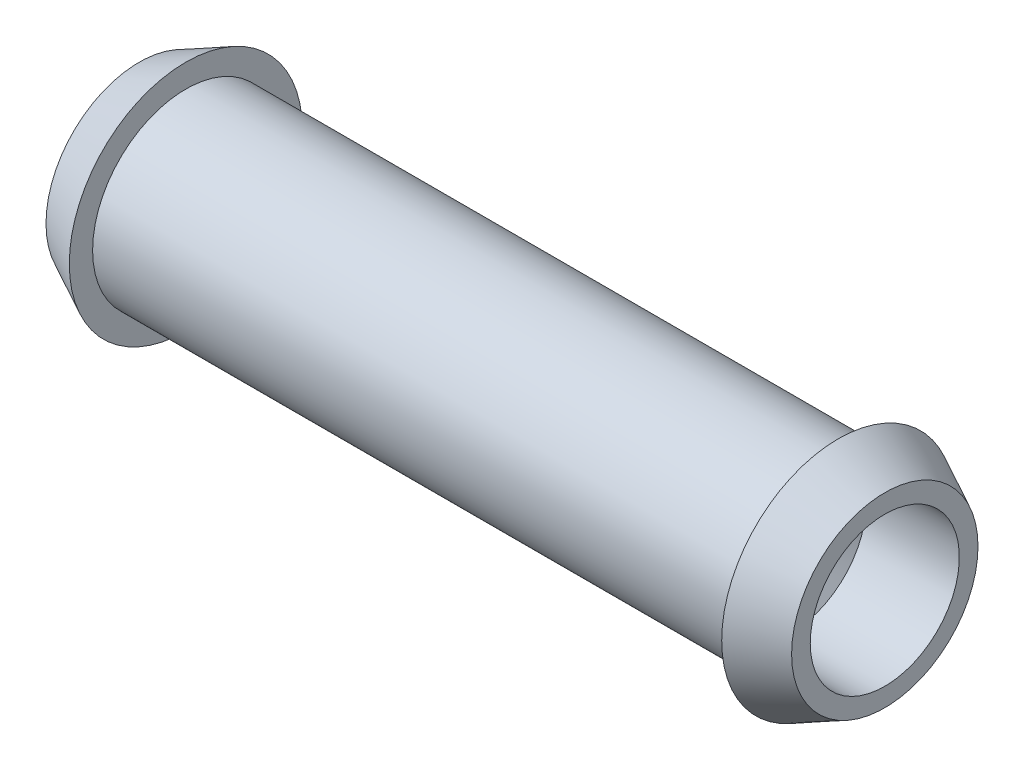
SolidWorks part; units mm, degrees
revolve "Cut-to-GripLength" cut sketch "Sketch2" angle 360 about L0
sketch "Sketch2" plane through (0, 0, 0) normal (0, 0, 1) x (1, 0, 0)
  line L0 (-30, 0) -> (30, 0) construction
  line L1 (-30, 0) -> (31, 0) construction
  line L3 (-21, 0) -> (-17.5, 0)
  line L4 (-21, 0) -> (-21, 6)
  line L5 (-21, 6) -> (-17.5, 6)
  line L6 (-17.5, 0) -> (-17.5, 6)
  line L7 (17.5, 0) -> (21, 0)
  line L8 (17.5, 0) -> (17.5, 6)
  line L9 (17.5, 6) -> (21, 6)
  line L10 (21, 0) -> (21, 6)
  dimension "GripLength" = 35
  dimension "D1" = 17.5
  dimension "D2" = 42
  dimension "D3" = 21
  dimension "D4" = 12
revolve "Base-Revolve" add sketch "Sketch1" angle 360 about L0
sketch "Sketch1" plane through (0, 0, 0) normal (0, 0, 1) x (1, 0, 0)
  line L0 (-30, 0) -> (31, 0) construction
  line L2 (-20, 0) -> (20, 0)
  line L3 (-20, 0) -> (-20, 5)
  line L4 (-20, 5) -> (20, 5)
  line L5 (20, 0) -> (20, 5)
  dimension "Length" = 40
  dimension "Diameter" = 10
ref_plane "Plane1" through (0, 0, 0) normal (0, 0, 1) x (1, 0, 0)
ref_plane "Plane2" through (0, 0, 0) normal (0, 1, 0) x (1, 0, 0)
ref_plane "Plane3" through (0, 0, 0) normal (1, 0, 0) x (0, 0, -1)
sketch "Sketch3" plane through (0, 0, 0) normal (0, 0, 1) x (1, 0, 0)
  line L0 (-23, 0) -> (23, 0) construction
  line L1 (-30, 0) -> (31, 0) construction
  line L2 (-20, 5) -> (-20, 0)
  line L3 (-20, 0) -> (-17.5, 0)
  line L4 (-20, 5) -> (-17.5, 6.25)
  line L5 (-17.5, 6.25) -> (-17.5, 0)
  line L6 (20, 5) -> (17.5, 6.25)
  line L7 (17.5, 6.25) -> (17.5, 0)
  line L10 (20, 5) -> (20, 0)
  line L11 (20, 0) -> (17.5, 0)
  line L12 (-17.5, 5) -> (-17.5, -5) construction
  line L13 (17.5, -5) -> (17.5, 5) construction
  dimension "D1" = 10
  dimension "D2" = 12.5
  dimension "D3" = 2.5
revolve "HeadTypeA" add sketch "Sketch3" angle 360 about L0
sketch "Sketch4" plane through (0, 0, 0) normal (0, 0, 1) x (1, 0, 0)
  line L0 (-20, 0) -> (20, 0) construction
  line L1 (-30, 0) -> (31, 0) construction
  line L2 (-17.5, 0) -> (-17.5, 6.25)
  line L3 (-17.5, 6.25) -> (-15.3349, 5)
  line L4 (-15.3349, 0) -> (-17.5, 0)
  line L5 (-17.5, -6.25) -> (-15.3349, -5) construction
  line L6 (0, 0) -> (0, 14) construction
  line L7 (15.3349, 0) -> (17.5, 0)
  line L8 (17.5, 0) -> (17.5, 6.25)
  line L9 (-15.3349, 5) -> (-15.3349, 0)
  line L10 (15.3349, 5) -> (15.3349, 0)
  line L11 (17.5, 6.25) -> (15.3349, 5)
  dimension "D2" = 12.5
  dimension "D1" = 10
  dimension "D3" = 60
  dimension "D4" = 35
revolve "HeadTypeB" [suppressed] add sketch "Sketch4" angle 360 about L0
sketch "Sketch5" plane through (0, 0, 0) normal (0, 0, 1) x (1, 0, 0)
  line L0 (-22, 0) -> (21, 0) construction
  line L1 (-30, 0) -> (31, 0) construction
  line L2 (-12.6906, 0) -> (-15, 4)
  line L4 (-15, 4) -> (-20, 4)
  line L5 (-20, 4) -> (-20, 0)
  line L6 (-20, 0) -> (-12.6906, 0)
  line L7 (12.6906, 0) -> (15, 4)
  line L8 (15, 4) -> (20, 4)
  line L9 (20, 4) -> (20, 0)
  line L10 (20, 0) -> (12.6906, 0)
  line L11 (-12.6906, 0) -> (-15, -4) construction
  line L12 (12.6906, 0) -> (15, -4) construction
  dimension "D1" = 40
  dimension "D2" = 20
  dimension "HoleDepth" = 5
  dimension "D3" = 5
  dimension "D4" = 120
  dimension "D5" = 120
  dimension "HoleDia" = 8
  dimension "D6" = 8
revolve "HoleTypeA" cut sketch "Sketch5" angle 360 about L0
sketch "Sketch6" plane through (0, 0, 0) normal (0, 0, 1) x (1, 0, 0)
  line L0 (-22, 0) -> (22, 0) construction
  line L1 (-30, 0) -> (31, 0) construction
  line L2 (-20, 5) -> (-17.1132, 0)
  line L4 (-17.1132, 0) -> (-20, 0)
  line L5 (-20, 0) -> (-20, 5)
  line L6 (-20, -5) -> (-17.1132, 0) construction
  line L7 (20, -5) -> (17.1132, 0) construction
  line L8 (17.1132, 0) -> (20, 0)
  line L9 (20, 0) -> (20, 5)
  line L10 (20, 5) -> (17.1132, 0)
  dimension "D1" = 120
  dimension "D2" = 10
  dimension "D3" = 120
  dimension "D4" = 40
  dimension "D5" = 20
revolve "HoleTypeB" [suppressed] cut sketch "Sketch6" angle 360 about L0
equation "\"D1@Sketch2\" = \"GripLength@Sketch2\" / 2"
equation "\"D2@Sketch2\" = \"Length@Sketch1\" + 2"
equation "\"D3@Sketch2\" = \"D2@Sketch2\" / 2"
equation "\"D4@Sketch2\" = \"Diameter@Sketch1\" + 2"
equation "\"D1@Sketch3\" = \"Diameter@Sketch1\""
equation "\"D2@Sketch3\" = \"Diameter@Sketch1\" * 1.25"
equation "\"D3@Sketch3\" = \"HeadHt@Sketch3\""
equation "\"D1@Sketch5\" = \"Length@Sketch1\""
equation "\"D2@Sketch5\" = \"D1@Sketch5\" / 2"
equation "\"D3@Sketch5\" = \"HoleDepth@Sketch5\""
equation "\"D5@Sketch5\" = \"D4@Sketch5\""
equation "\"D6@Sketch5\" = \"HoleDia@Sketch5\""
equation "\"D2@Sketch6\" = \"Diameter@Sketch1\""
equation "\"D3@Sketch6\" = \"D1@Sketch6\""
equation "\"D4@Sketch6\" = \"Length@Sketch1\""
equation "\"D5@Sketch6\" = \"D4@Sketch6\" / 2"
equation "\"D1@Sketch4\" = \"Diameter@Sketch1\""
equation "\"D2@Sketch4\" = \"Diameter@Sketch1\" * 1.25"
equation "\"D4@Sketch4\" = \"GripLength@Sketch2\""
